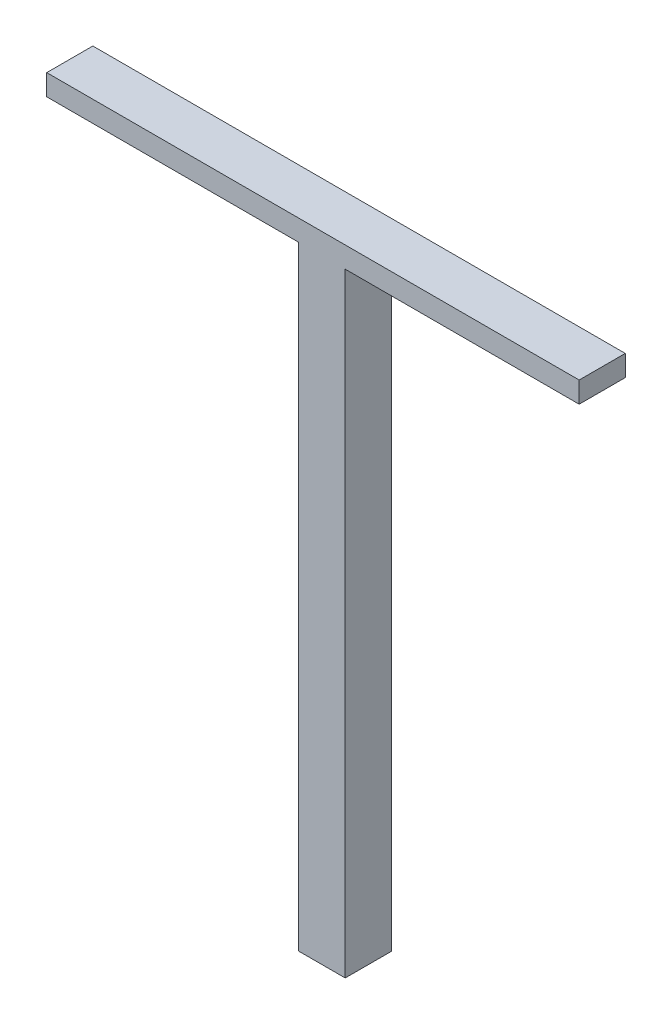
SolidWorks part; units mm, degrees
ref_plane "Спереди" through (0, 0, 0) normal (0, 0, 1) x (1, 0, 0)
ref_plane "Сверху" through (0, 0, 0) normal (0, 1, 0) x (1, 0, 0)
ref_plane "Справа" through (0, 0, 0) normal (1, 0, 0) x (0, 0, -1)
sketch "Эскиз1" plane through (0, 0, 0) normal (0, 0, 1) x (1, 0, 0)
  line L0 (-73.8951, 42.9213) -> (388.1681, 42.9213)
  line L1 (388.1681, 42.9213) -> (388.1681, 24.7184)
  line L2 (388.1681, 24.7184) -> (185.1334, 24.7184)
  line L3 (185.1334, 24.7184) -> (185.1334, -508.025)
  line L4 (185.1334, -508.025) -> (144.4151, -508.025)
  line L5 (144.4151, -508.025) -> (144.4151, 24.7184)
  line L6 (144.4151, 24.7184) -> (-73.8951, 24.7184)
  line L7 (-73.8951, 24.7184) -> (-73.8951, 42.9213)
extrude "Бобышка-Вытянуть1" add sketch "Эскиз1" along normal blind 40
